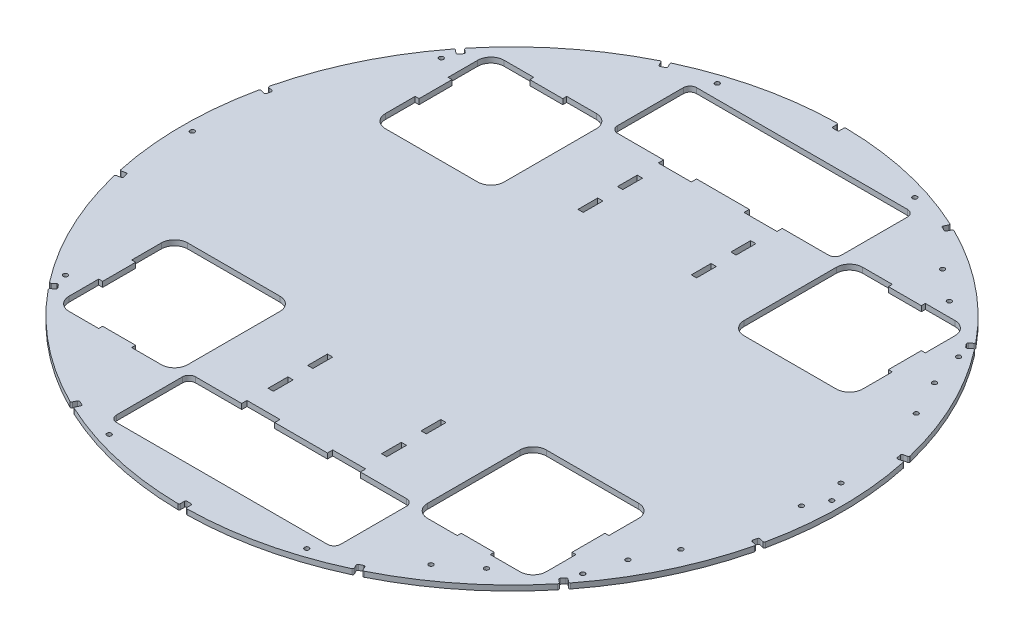
SolidWorks part; units mm, degrees
ref_plane "Front Plane" through (0, 0, 0) normal (0, 0, 1) x (1, 0, 0)
ref_plane "Top Plane" through (0, 0, 0) normal (0, 1, 0) x (1, 0, 0)
ref_plane "Right Plane" through (0, 0, 0) normal (1, 0, 0) x (0, 0, -1)
sketch "Sketch1" plane through (0, 0, 0) normal (0, 1, 0) x (1, 0, 0)
  circle A0 centre (0, 0) radius 250
extrude "Boss-Extrude1" add sketch "Sketch1" along normal blind 4
sketch "Sketch2" plane through (0, 4, 0) normal (0, 1, 0) x (1, 0, 0)
  line L0 (0, -250) -> (0, 250) construction
  line L1 (80, 220) -> (-80, 220)
  line L2 (85, 215) -> (85, 165)
  line L3 (80, 160) -> (-80, 160)
  line L4 (-85, 215) -> (-85, 165)
  line L5 (85, 220) -> (-85, 160) construction
  line L6 (85, 160) -> (-85, 220) construction
  line L7 (-55, 0) -> (55, 0) construction
  line L8 (85, -215) -> (85, -165)
  line L9 (80, -160) -> (-80, -160)
  line L10 (-85, -215) -> (-85, -165)
  line L11 (80, -220) -> (-80, -220)
  circle A0 centre (0, 0) radius 250 construction
  arc A1 (-80, 160) -> (-85, 165) centre (-80, 165) cw
  arc A2 (80, 160) -> (85, 165) centre (80, 165) ccw
  arc A3 (85, 215) -> (80, 220) centre (80, 215) ccw
  arc A4 (-80, 220) -> (-85, 215) centre (-80, 215) ccw
  arc A5 (-85, -215) -> (-80, -220) centre (-80, -215) ccw
  arc A6 (80, -220) -> (85, -215) centre (80, -215) ccw
  arc A7 (85, -165) -> (80, -160) centre (80, -165) ccw
  arc A8 (-80, -160) -> (-85, -165) centre (-80, -165) ccw
  point P0 (0, 190)
  point P33 (-85, -220)
  point P36 (85, -220)
  point P39 (85, -160)
  point P42 (-85, -160)
  dimension "D4" = 5
  dimension "D5" = 5
  dimension "D1" = 170
  dimension "D2" = 190
  dimension "D3" = 60
extrude "Cut-Extrude1" cut sketch "Sketch2" against normal blind 10
sketch "Sketch3" plane through (0, 4, 0) normal (0, 1, 0) x (1, 0, 0)
  line L0 (45, 160) -> (-45, 160)
  line L1 (-80, 160) -> (80, 160) construction
  line L2 (0, -2.2) -> (0, 2.2) construction
  line L3 (-45, 160) -> (-20, 160)
  line L4 (-45, 160) -> (-45, 156)
  line L5 (-45, 156) -> (-20, 156)
  line L6 (-20, 160) -> (-20, 156)
  line L7 (20, 160) -> (20, 156)
  line L8 (45, 156) -> (20, 156)
  line L9 (45, 160) -> (45, 156)
  line L10 (45, 160) -> (20, 160)
  line L11 (-2.2, 0) -> (2.2, 0) construction
  line L12 (45, -160) -> (20, -160)
  line L13 (45, -160) -> (45, -156)
  line L14 (45, -156) -> (20, -156)
  line L15 (20, -160) -> (20, -156)
  line L16 (-20, -160) -> (-20, -156)
  line L17 (-45, -156) -> (-20, -156)
  line L18 (-45, -160) -> (-45, -156)
  line L19 (-45, -160) -> (-20, -160)
  line L20 (45, -160) -> (-45, -160)
  point P5 (0, 160)
  point P24 (0, -160)
  line M7 (80, 160) -> (-80, 160)
  line M10 (-80, -160) -> (80, -160)
  dimension "D2" = 4
  dimension "D3" = 25
extrude "Cut-Extrude2" cut sketch "Sketch3" against normal blind 5 contours L6 L0 L4 L5 | L9 L7 L8 M7 | L18 L16 L17 M10 | L15 L13 L14 M10
sketch "Sketch4" plane through (0, 4, 0) normal (0, 1, 0) x (1, 0, 0)
  line L0 (45, 160) -> (-45, 160)
  line L3 (80, 220) -> (-80, 220) construction
  line L4 (45, 160) -> (80, 160) construction
  line L5 (45, 140) -> (41, 140)
  line L6 (45, 140) -> (45, 125)
  line L7 (45, 125) -> (41, 125)
  line L8 (41, 140) -> (41, 125)
  line L9 (0, -2.2) -> (0, 2.2) construction
  line L10 (41, 110) -> (45, 110)
  line L11 (41, 110) -> (41, 95)
  line L12 (41, 95) -> (45, 95)
  line L13 (45, 110) -> (45, 95)
  line L14 (-45, 110) -> (-45, 95)
  line L15 (-41, 95) -> (-45, 95)
  line L16 (-41, 110) -> (-41, 95)
  line L17 (-41, 110) -> (-45, 110)
  line L18 (-41, 140) -> (-41, 125)
  line L19 (-45, 125) -> (-41, 125)
  line L20 (-45, 140) -> (-45, 125)
  line L21 (-45, 140) -> (-41, 140)
  line L22 (-2.2, 0) -> (2.2, 0) construction
  line L23 (-45, -140) -> (-41, -140)
  line L24 (-45, -140) -> (-45, -125)
  line L25 (-45, -125) -> (-41, -125)
  line L26 (-41, -140) -> (-41, -125)
  line L27 (-41, -110) -> (-45, -110)
  line L28 (-41, -110) -> (-41, -95)
  line L29 (-41, -95) -> (-45, -95)
  line L30 (-45, -110) -> (-45, -95)
  line L31 (45, -110) -> (45, -95)
  line L32 (41, -95) -> (45, -95)
  line L33 (41, -110) -> (41, -95)
  line L34 (41, -110) -> (45, -110)
  line L35 (41, -140) -> (41, -125)
  line L36 (45, -125) -> (41, -125)
  line L37 (45, -140) -> (45, -125)
  line L38 (45, -140) -> (41, -140)
  point P3 (0, 160)
  point P5 (0, 220)
  point P16 (45, 132.5)
  point P17 (45, 102.5)
  dimension "D1" = 0
  dimension "D2" = 4
  dimension "D3" = 0
  dimension "D4" = 90
  dimension "D5" = 15
  dimension "D6" = 20
  dimension "D7" = 15
  dimension "D8" = 4
  dimension "D9" = 30
extrude "Cut-Extrude3" cut sketch "Sketch4" against normal blind 20 contours L5 L8 L7 L6 | L13 L10 L11 L12 | L21 L20 L19 L18 | L16 L17 L14 L15 | L30 L27 L28 L29 | L23 L26 L25 L24 | L33 L34 L31 L32 | L38 L37 L36 L35
sketch "Sketch7" plane through (0, 4, 0) normal (0, 1, 0) x (1, 0, 0)
  line L0 (0, -2.2) -> (0, 2.2) construction
  line L1 (-101, 75) -> (-171, 75)
  line L2 (-91, 85) -> (-91, 155)
  line L3 (-101, 165) -> (-171, 165)
  line L4 (-181, 85) -> (-181, 155)
  line L5 (-91, 75) -> (-181, 165) construction
  line L6 (-91, 165) -> (-181, 75) construction
  line L7 (91, 165) -> (181, 75) construction
  line L8 (91, 75) -> (181, 165) construction
  line L9 (181, 85) -> (181, 155)
  line L10 (101, 165) -> (171, 165)
  line L11 (91, 85) -> (91, 155)
  line L12 (101, 75) -> (171, 75)
  line L13 (-2.2, 0) -> (2.2, 0) construction
  line L14 (91, -75) -> (181, -165) construction
  line L15 (91, -165) -> (181, -75) construction
  line L16 (101, -75) -> (171, -75)
  line L17 (91, -85) -> (91, -155)
  line L18 (101, -165) -> (171, -165)
  line L19 (181, -85) -> (181, -155)
  line L20 (-91, -165) -> (-181, -75) construction
  line L21 (-91, -75) -> (-181, -165) construction
  line L22 (-181, -85) -> (-181, -155)
  line L23 (-101, -165) -> (-171, -165)
  line L24 (-91, -85) -> (-91, -155)
  line L25 (-101, -75) -> (-171, -75)
  arc A0 (-171, 165) -> (-181, 155) centre (-171, 155) ccw
  arc A1 (-91, 155) -> (-101, 165) centre (-101, 155) ccw
  arc A2 (-181, -155) -> (-171, -165) centre (-171, -155) ccw
  arc A3 (-101, -165) -> (-91, -155) centre (-101, -155) ccw
  arc A4 (-91, -85) -> (-101, -75) centre (-101, -85) ccw
  arc A5 (-171, -75) -> (-181, -85) centre (-171, -85) ccw
  arc A6 (91, -155) -> (101, -165) centre (101, -155) ccw
  arc A7 (171, -165) -> (181, -155) centre (171, -155) ccw
  arc A8 (181, -85) -> (171, -75) centre (171, -85) ccw
  arc A9 (101, -75) -> (91, -85) centre (101, -85) ccw
  arc A10 (101, 75) -> (91, 85) centre (101, 85) cw
  arc A11 (171, 75) -> (181, 85) centre (171, 85) ccw
  arc A12 (181, 155) -> (171, 165) centre (171, 155) ccw
  arc A13 (91, 155) -> (101, 165) centre (101, 155) cw
  arc A14 (-171, 75) -> (-181, 85) centre (-171, 85) cw
  arc A15 (-101, 75) -> (-91, 85) centre (-101, 85) ccw
  point P0 (-136, 120)
  point P12 (136, 120)
  point P19 (136, -120)
  point P24 (-136, -120)
  dimension "D5" = 10
  dimension "D6" = 10
  dimension "D7" = 10
  dimension "D1" = 90
  dimension "D2" = 90
  dimension "D3" = 136
  dimension "D4" = 120
extrude "Cut-Extrude4" cut sketch "Sketch7" against normal blind 5
sketch "Sketch8" plane through (0, 4, 0) normal (0, 1, 0) x (1, 0, 0)
  line L0 (-181, 155) -> (-181, 85) construction
  line L1 (-178, 107.5) -> (-184, 107.5)
  line L2 (-178, 107.5) -> (-178, 132.5)
  line L3 (-178, 132.5) -> (-184, 132.5)
  line L4 (-184, 107.5) -> (-184, 132.5)
  line L5 (-178, 107.5) -> (-184, 132.5) construction
  line L6 (-178, 132.5) -> (-184, 107.5) construction
  line L7 (-101, 165) -> (-171, 165) construction
  line L8 (-123.5, 162) -> (-148.5, 162)
  line L9 (-123.5, 162) -> (-123.5, 168)
  line L10 (-123.5, 168) -> (-148.5, 168)
  line L11 (-148.5, 162) -> (-148.5, 168)
  line L12 (-123.5, 162) -> (-148.5, 168) construction
  line L13 (-123.5, 168) -> (-148.5, 162) construction
  line L14 (0, -2.2) -> (0, 2.2) construction
  line L15 (123.5, 168) -> (148.5, 162) construction
  line L16 (123.5, 162) -> (148.5, 168) construction
  line L17 (178, 132.5) -> (184, 107.5) construction
  line L18 (178, 107.5) -> (184, 132.5) construction
  line L19 (148.5, 162) -> (148.5, 168)
  line L20 (123.5, 168) -> (148.5, 168)
  line L21 (123.5, 162) -> (123.5, 168)
  line L22 (123.5, 162) -> (148.5, 162)
  line L23 (184, 107.5) -> (184, 132.5)
  line L24 (178, 132.5) -> (184, 132.5)
  line L25 (178, 107.5) -> (178, 132.5)
  line L26 (178, 107.5) -> (184, 107.5)
  line L27 (-2.2, 0) -> (2.2, 0) construction
  line L28 (178, -107.5) -> (184, -132.5) construction
  line L29 (178, -132.5) -> (184, -107.5) construction
  line L30 (123.5, -162) -> (148.5, -168) construction
  line L31 (123.5, -168) -> (148.5, -162) construction
  line L32 (178, -107.5) -> (184, -107.5)
  line L33 (178, -107.5) -> (178, -132.5)
  line L34 (178, -132.5) -> (184, -132.5)
  line L35 (184, -107.5) -> (184, -132.5)
  line L36 (123.5, -162) -> (148.5, -162)
  line L37 (123.5, -162) -> (123.5, -168)
  line L38 (123.5, -168) -> (148.5, -168)
  line L39 (148.5, -162) -> (148.5, -168)
  line L40 (-123.5, -168) -> (-148.5, -162) construction
  line L41 (-123.5, -162) -> (-148.5, -168) construction
  line L42 (-178, -132.5) -> (-184, -107.5) construction
  line L43 (-178, -107.5) -> (-184, -132.5) construction
  line L44 (-148.5, -162) -> (-148.5, -168)
  line L45 (-123.5, -168) -> (-148.5, -168)
  line L46 (-123.5, -162) -> (-123.5, -168)
  line L47 (-123.5, -162) -> (-148.5, -162)
  line L48 (-184, -107.5) -> (-184, -132.5)
  line L49 (-178, -132.5) -> (-184, -132.5)
  line L50 (-178, -107.5) -> (-178, -132.5)
  line L51 (-178, -107.5) -> (-184, -107.5)
  point P0 (-181, 120)
  point P7 (-136, 165)
  point P24 (136, 165)
  point P25 (181, 120)
  point P36 (181, -120)
  point P37 (136, -165)
  point P46 (-136, -165)
  point P47 (-181, -120)
  dimension "D1" = 6
  dimension "D2" = 25
  dimension "D3" = 6
  dimension "D4" = 25
extrude "Boss-Extrude2" add sketch "Sketch8" against normal blind 4
sketch "Sketch11" plane through (0, 4, 0) normal (0, 1, 0) x (1, 0, 0)
  line L1 (1.5, 245) -> (-1.5, 245)
  line L2 (2.5, 246) -> (2.5, 255)
  line L3 (2.5, 255) -> (-2.5, 255)
  line L4 (-2.5, 246) -> (-2.5, 255)
  line L5 (2.5, 245) -> (-2.5, 255) construction
  line L6 (2.5, 255) -> (-2.5, 245) construction
  circle A0 centre (0, 0) radius 250 construction
  arc A1 (2.5, 246) -> (1.5, 245) centre (1.5, 246) cw
  arc A2 (-1.5, 245) -> (-2.5, 246) centre (-1.5, 246) cw
  point P0 (0, 250)
  dimension "D3" = 1
  dimension "D1" = 10
  dimension "D2" = 5
extrude "Cut-Extrude5" cut sketch "Sketch11" against normal blind 4
fillet "Fillet1" radius 1 2 edges at (2.5, 2, -249.9875) (-2.5, 2, -249.9875)
pattern_circular "CirPattern1" count 14 over 360 about axis through (0, 0, 0) along (0, 1, 0) of "Cut-Extrude5", "Fillet1"
sketch "Sketch12" plane through (0, 4, 0) normal (0, 1, 0) x (1, 0, 0)
  circle A1 centre (0, 0) radius 242.5
  circle A3 centre (-242.5, 0) radius 1.7
  dimension "D2" = 485
extrude "Cut-Extrude6" cut sketch "Sketch12" against normal blind 10 contours A1 A3 | A1 A3
pattern_circular "CirPattern2" count 10 over 360 about axis through (0, 0, 0) along (0, 1, 0) of "Cut-Extrude6"
sketch "Sketch13" plane through (0, 4, 0) normal (0, 1, 0) x (1, 0, 0)
  line L0 (-2.2, 0) -> (2.2, 0) construction
  line L1 (0, 0) -> (234.5, -15) construction
  line L2 (0, 0) -> (204.1916, -116.2799) construction
  line L3 (0, 0) -> (234.5, -15) construction
  line L4 (0, 0) -> (217.3428, 89.3161) construction
  circle A0 centre (234.5, 15) radius 1.7
  circle A1 centre (242.5, 0) radius 1.7 construction
  circle A2 centre (234.5, -15) radius 1.7
  circle A3 centre (217.3428, -89.3161) radius 1.7
  circle A4 centre (204.1916, -116.2799) radius 1.7
  circle A5 centre (156.1928, -175.5536) radius 1.7
  circle A6 centre (132.5525, -194.0234) radius 1.7
  circle A7 centre (204.1916, 116.2799) radius 1.7
  circle A8 centre (217.3428, 89.3161) radius 1.7
  circle A9 centre (132.5525, 194.0234) radius 1.7
  circle A10 centre (156.1928, 175.5536) radius 1.7
  dimension "D1" = 15
  dimension "D2" = 8
  dimension "D4" = 26
  dimension "D6" = 26
  dimension "D3" = 3
  dimension "D5" = 3
extrude "Cut-Extrude7" cut sketch "Sketch13" against normal blind 10
